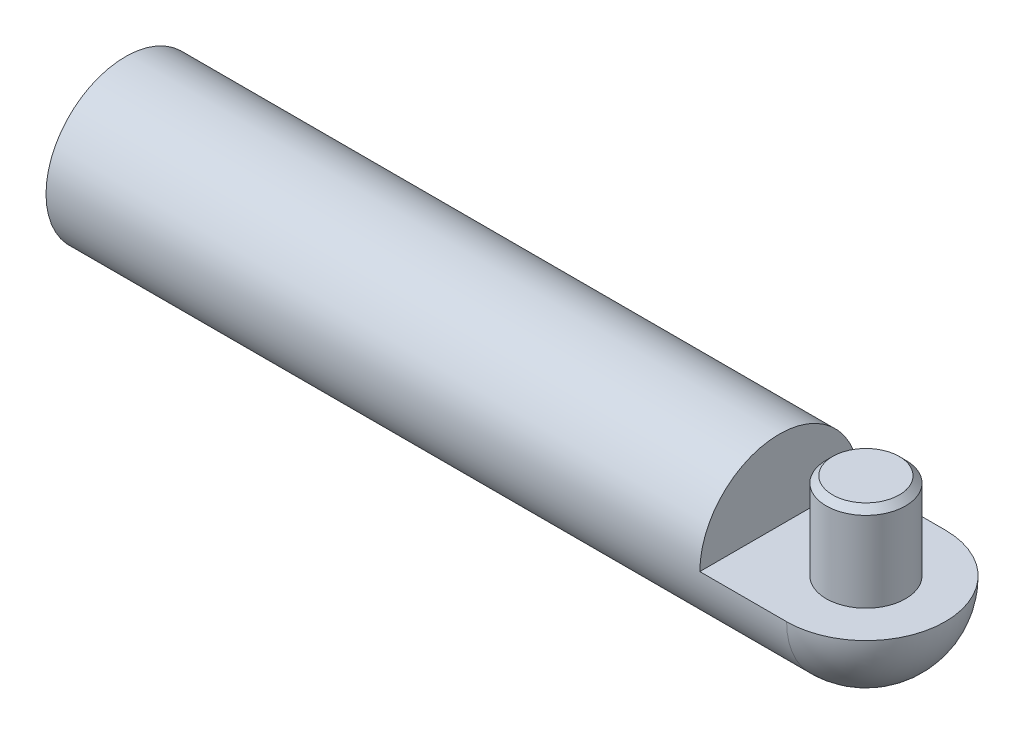
SolidWorks part; units mm, degrees
ref_plane "Front Plane" through (0, 0, 0) normal (0, 0, 1) x (1, 0, 0)
ref_plane "Top Plane" through (0, 0, 0) normal (0, 1, 0) x (1, 0, 0)
ref_plane "Right Plane" through (0, 0, 0) normal (1, 0, 0) x (0, 0, -1)
sketch "Sketch17" plane through (0, 0, 0) normal (1, 0, 0) x (0, 0, -1)
  line L0 (19.05, 0) -> (-19.05, 0)
  arc A0 (-19.05, 0) -> (19.05, 0) centre (0, 0) ccw
  dimension "D1" = 38.1
revolve "Revolve3" add sketch "Sketch17" angle 90 about L0
ref_plane "Plane5" through (0, 0, 0) normal (-1, 0, 0) x (0, 0, 1)
sketch "Sketch18" plane through (0, 0, 0) normal (-1, 0, 0) x (0, 0, 1)
  circle A0 centre (0, 0) radius 19.05
extrude "Boss-Extrude5" add sketch "Sketch18" along normal blind 177.8
ref_plane "Plane6" through (0, 0, 0) normal (1, 0, 0) x (0, 0, -1)
sketch "Sketch20" plane through (0, 0, 0) normal (1, 0, 0) x (0, 0, -1)
  line L0 (19.05, 0) -> (-19.05, 0) construction
  line L1 (-19.05, 0) -> (19.05, 0)
  arc A0 (19.05, 0) -> (-19.05, 0) centre (0, 0) ccw
extrude "Cut-Extrude4" cut sketch "Sketch20" against normal blind 20.828
ref_plane "Plane7" through (0, 0, 0) normal (0, 1, 0) x (1, 0, 0)
sketch "Sketch21" plane through (0, 0, 0) normal (0, 1, 0) x (1, 0, 0)
  line L1 (0, 19.05) -> (0, -19.05) construction
  line L2 (-20.828, -19.05) -> (-20.828, 19.05) construction
  circle A0 centre (0, 0) radius 9.525
  dimension "D1" = 19.05
  dimension "D2" = 20.828
extrude "Boss-Extrude6" add sketch "Sketch21" along normal blind 20.828
chamfer "Chamfer2" distance 1.524 angle 45 1 edges at (-9.525, 20.828, 0)
